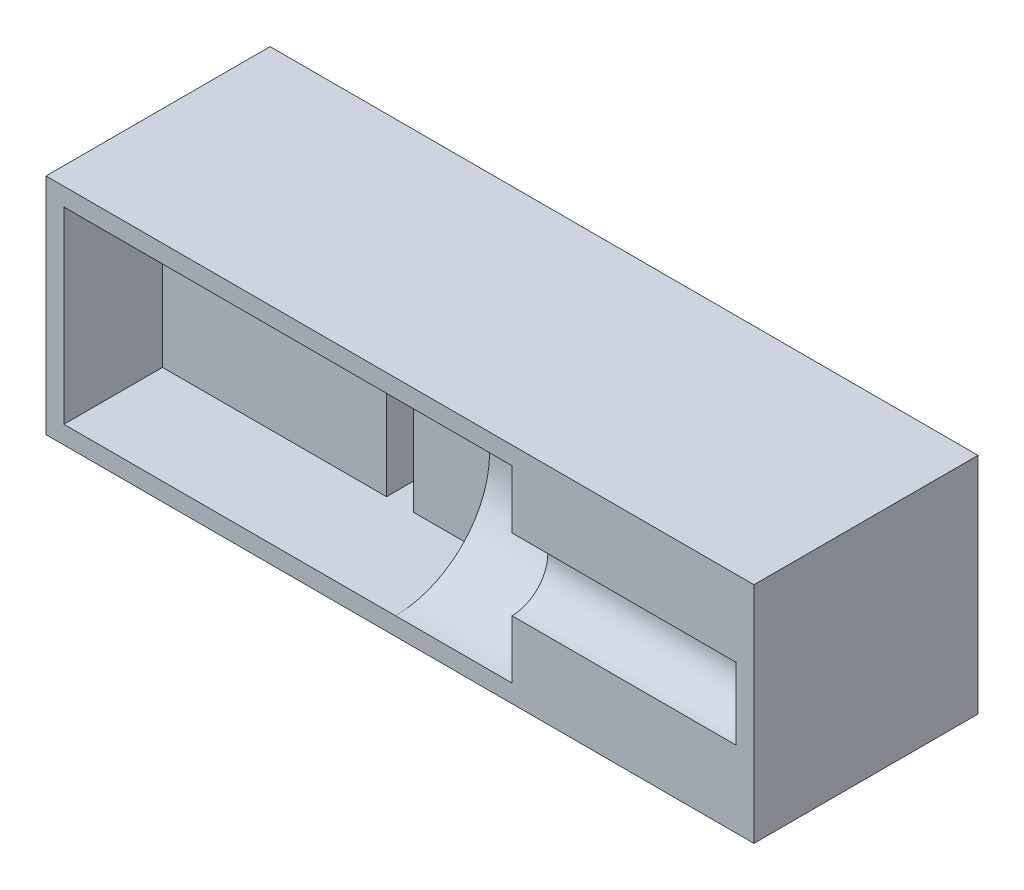
SolidWorks part; units mm, degrees
ref_plane "Front Plane" through (0, 0, 0) normal (0, 0, 1) x (1, 0, 0)
ref_plane "Top Plane" through (0, 0, 0) normal (0, 1, 0) x (1, 0, 0)
ref_plane "Right Plane" through (0, 0, 0) normal (1, 0, 0) x (0, 0, -1)
sketch "Sketch1" plane through (0, 0, 0) normal (0, 0, 1) x (1, 0, 0)
  line L1 (-30, -12.5) -> (20, -12.5)
  line L2 (-30, -12.5) -> (-30, 12.5)
  line L3 (-30, 12.5) -> (20, 12.5)
  line L4 (20, -12.5) -> (20, 12.5)
  point P0 (0, 0)
  dimension "D1" = 50
  dimension "D2" = 25
extrude "Boss-Extrude1" add sketch "Sketch1" along normal blind 25
sketch "Sketch2" plane through (0, 0, 25) normal (0, 0, 1) x (1, 0, 0)
  line L0 (-30, -12.5) -> (20, -12.5) construction
  line L1 (-28, 10.5) -> (9, 10.5)
  line L2 (-28, 10.5) -> (-28, -10.5)
  line L3 (-28, -10.5) -> (9, -10.5)
  line L4 (9, 10.5) -> (9, -10.5)
  line L5 (-30, 12.5) -> (-30, -12.5) construction
  dimension "D1" = 21
  dimension "D2" = 2
  dimension "D3" = 2
  dimension "D4" = 37
extrude "Cut-Extrude1" cut sketch "Sketch2" against normal blind 11
sketch "Sketch3" plane through (0, 0, 14) normal (0, 0, 1) x (1, 0, 0)
  line L0 (9, 10.5) -> (-28, 10.5) construction
  line L1 (-3, 10.5) -> (0, 10.5)
  line L2 (-3, 10.5) -> (-3, -10.5)
  line L3 (-3, -10.5) -> (0, -10.5)
  line L4 (0, 10.5) -> (0, -10.5)
  line L5 (-28, -10.5) -> (9, -10.5) construction
  line L6 (-28, 10.5) -> (-28, -10.5) construction
  dimension "D1" = 25
  dimension "D2" = 3
extrude "Cut-Extrude2" cut sketch "Sketch3" against normal blind 8
sketch "Sketch7" plane through (20, 0, 0) normal (1, 0, 0) x (0, 0, -1)
  line L1 (-25, 12.5) -> (0, 12.5)
  line L2 (-25, 12.5) -> (-25, -12.5)
  line L3 (-25, -12.5) -> (0, -12.5)
  line L4 (0, 12.5) -> (0, -12.5)
extrude "Boss-Extrude2" add sketch "Sketch7" along normal blind 19
sketch "Sketch8" plane through (9, 0, 0) normal (-1, 0, 0) x (0, 0, 1)
  line L0 (25, -10.5) -> (25, 10.5) construction
  line L1 (25, -10.5) -> (25, 10.5)
  arc A0 (25, 10.5) -> (25, -10.5) centre (25, 0) ccw
extrude "Cut-Extrude3" cut sketch "Sketch8" against normal blind 13
sketch "Sketch9" plane through (22, 0, 0) normal (-1, 0, 0) x (0, 0, 1)
  line L0 (25, -10.5) -> (25, 10.5) construction
  line L1 (25, 4) -> (25, -4)
  arc A1 (25, 4) -> (25, -4) centre (25, 0) ccw
  dimension "D1" = 8
sketch "Sketch10" plane through (39, 0, 0) normal (1, 0, 0) x (0, 0, -1)
  line L1 (0, -12.5) -> (-25, -12.5)
  line L2 (0, -12.5) -> (0, 12.5)
  line L3 (0, 12.5) -> (-25, 12.5)
  line L4 (-25, -12.5) -> (-25, 12.5)
extrude "Boss-Extrude3" add sketch "Sketch10" along normal blind 10
extrude "Cut-Extrude5" cut sketch "Sketch9" against normal blind 25
